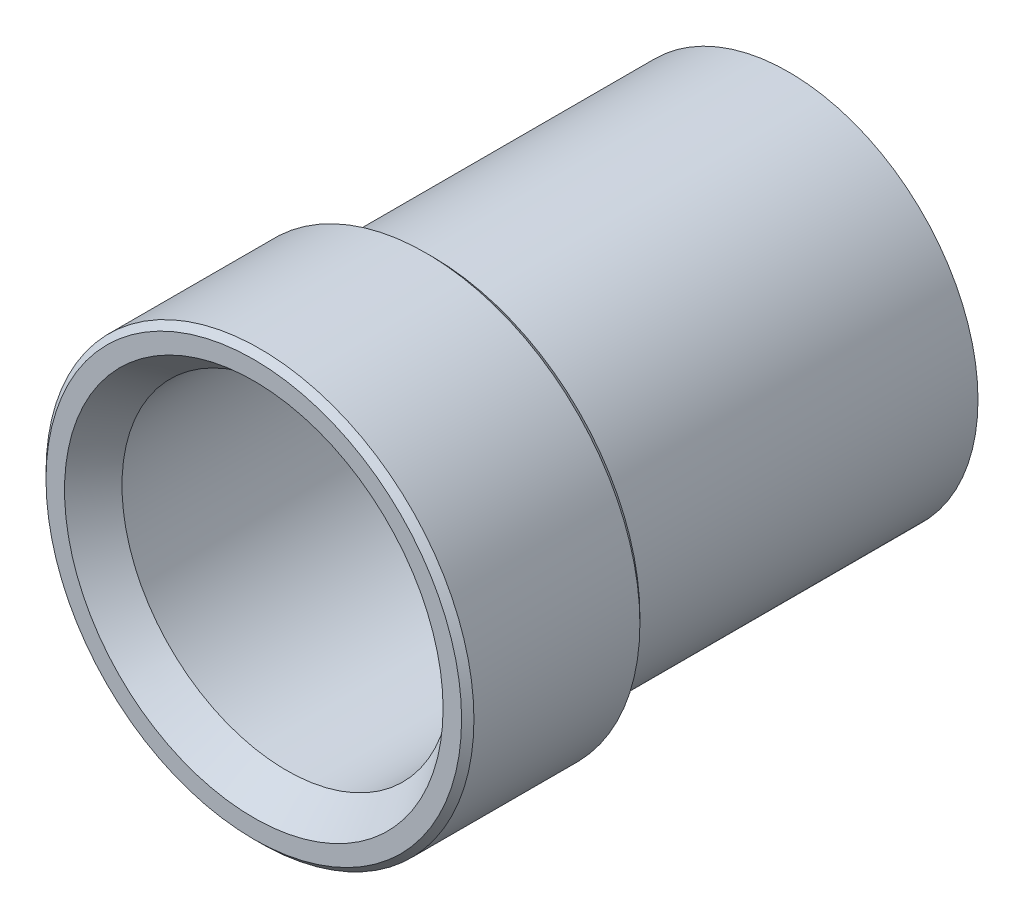
SolidWorks part; units mm, degrees
ref_plane "Front Plane" through (0, 0, 0) normal (0, 0, 1) x (1, 0, 0)
ref_plane "Top Plane" through (0, 0, 0) normal (0, 1, 0) x (1, 0, 0)
ref_plane "Right Plane" through (0, 0, 0) normal (1, 0, 0) x (0, 0, -1)
sketch "Sketch1" plane through (0, 0, 0) normal (1, 0, 0) x (0, 0, -1)
  line L0 (-5.1594, 0) -> (5.1594, 0) construction
  line L1 (-5.1594, 3.6513) -> (-5.1594, 4.1275) construction
  line L2 (-5.1594, 4.1275) -> (-1.7198, 4.1275) construction
  line L3 (-1.7198, 4.1275) -> (-1.7198, 3.6513) construction
  line L4 (-1.7198, 3.6513) -> (5.1594, 3.6513) construction
  line L5 (5.1594, 3.6513) -> (5.1594, 3.175) construction
  line L6 (5.1594, 3.175) -> (-4.5274, 3.175) construction
  line L7 (-4.5274, 3.175) -> (-5.1594, 3.6513) construction
  dimension "Flared Angle" = 37
  dimension "Length" = 10.3187
  dimension "Base Length" = 3.4396
  dimension "Thread Inner Diameter" = 8.255
  dimension "For Tube OD" = 6.35
sketch "Sketch2" plane through (0, 0, 0) normal (1, 0, 0) x (0, 0, -1)
  line L0 (-4.5274, 3.175) -> (-5.1594, 3.6513)
  line L1 (-5.1594, 3.6513) -> (-5.1594, 4.1275)
  line L2 (-5.1594, 4.1275) -> (-1.7198, 4.1275)
  line L3 (-1.7198, 4.1275) -> (-1.7198, 3.6513)
  line L4 (-1.7198, 3.6513) -> (5.1594, 3.6513)
  line L5 (5.1594, 3.6513) -> (5.1594, 3.175)
  line L6 (5.1594, 3.175) -> (-4.5274, 3.175)
revolve "Revolve1" add sketch "Sketch2" angle 360 about L0
chamfer "Chamfer1" distance 0.1191 angle 45 2 edges at (4.1275, 0, 5.1594) (4.1275, 0, 1.7198)
equation "\"D1@Chamfer1\"=(\"Thread Inner Diameter@Sketch1\"-\"For Tube OD@Sketch1\")/16"
equation "\"Base Length@Sketch1\"=\"Length@Sketch1\"/3"
equation "\"Thread Inner Diameter@Sketch1\"=\"For Tube OD@Sketch1\"*1.3"
